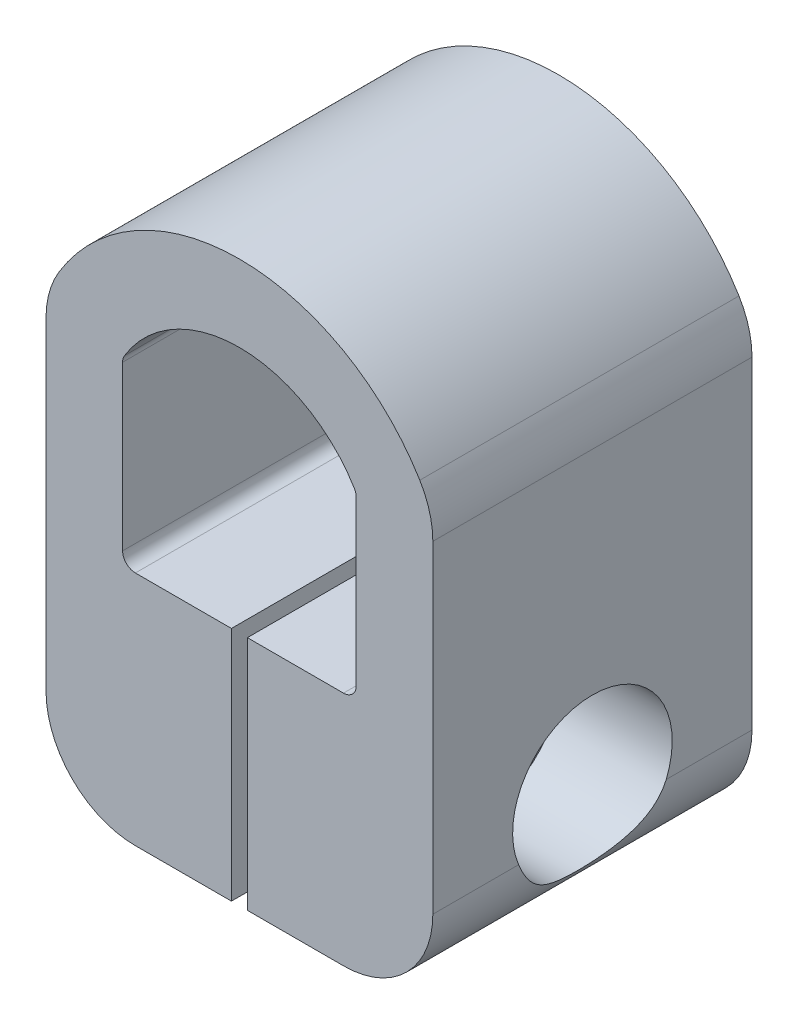
SolidWorks part; units mm, degrees
ref_plane "Front Plane" through (0, 0, 0) normal (0, 0, 1) x (1, 0, 0)
ref_plane "Top Plane" through (0, 0, 0) normal (0, 1, 0) x (1, 0, 0)
ref_plane "Right Plane" through (0, 0, 0) normal (1, 0, 0) x (0, 0, -1)
sketch "Sketch1" plane through (0, 0, 0) normal (0, 0, 1) x (1, 0, 0)
  line L0 (-15.3924, 13.7607) -> (-15.3924, 0.762)
  line L2 (15.3924, 0.762) -> (15.3924, 13.7607)
  line L3 (-9.2964, 13.7607) -> (-9.2964, 0.762)
  line L4 (-8.2804, -0.254) -> (8.2804, -0.254)
  line L5 (9.2964, 0.762) -> (9.2964, 13.7607)
  line L6 (-9.0424, 13.7607) -> (-9.0424, 0.762)
  line L7 (-8.2804, 0) -> (8.2804, 0)
  line L8 (9.0424, 0.762) -> (9.0424, 13.7607)
  line L9 (-8.2804, -19.05) -> (8.2804, -19.05)
  line L10 (-15.3924, 0.762) -> (-15.3924, -11.938)
  line L11 (15.3924, -11.938) -> (15.3924, 0.762)
  line L13 (-8.2804, -6.35) -> (8.2804, -6.35) construction
  arc A2 (15.3924, 13.7607) -> (14.356, 17.4577) centre (8.2804, 13.7607) ccw
  arc A3 (14.356, 17.4577) -> (-14.356, 17.4577) centre (0, 8.7221) ccw
  arc A4 (-14.356, 17.4577) -> (-15.3924, 13.7607) centre (-8.2804, 13.7607) ccw
  arc A5 (-9.2964, 0.762) -> (-8.2804, -0.254) centre (-8.2804, 0.762) ccw
  arc A6 (8.2804, -0.254) -> (9.2964, 0.762) centre (8.2804, 0.762) ccw
  arc A7 (9.2964, 13.7607) -> (9.1483, 14.2889) centre (8.2804, 13.7607) ccw
  arc A8 (9.1483, 14.2889) -> (-9.1483, 14.2889) centre (0, 8.7221) ccw
  arc A9 (-9.1483, 14.2889) -> (-9.2964, 13.7607) centre (-8.2804, 13.7607) ccw
  arc A10 (8.9314, 14.1568) -> (-8.9314, 14.1568) centre (0, 8.7221) ccw
  arc A11 (-8.9314, 14.1568) -> (-9.0424, 13.7607) centre (-8.2804, 13.7607) ccw
  arc A12 (-9.0424, 0.762) -> (-8.2804, 0) centre (-8.2804, 0.762) ccw
  arc A13 (8.2804, 0) -> (9.0424, 0.762) centre (8.2804, 0.762) ccw
  arc A14 (9.0424, 13.7607) -> (8.9314, 14.1568) centre (8.2804, 13.7607) ccw
  arc A15 (-15.3924, -11.938) -> (-8.2804, -19.05) centre (-8.2804, -11.938) ccw
  arc A16 (8.2804, -19.05) -> (15.3924, -11.938) centre (8.2804, -11.938) ccw
  arc A17 (8.2804, -6.35) -> (15.3924, 0.762) centre (8.2804, 0.762) ccw construction
  arc A18 (-15.3924, 0.762) -> (-8.2804, -6.35) centre (-8.2804, 0.762) ccw construction
  dimension "D3" = 12.7
  dimension "D4" = 12.7
  dimension "D1" = 6.35
  dimension "D2" = 0.254
extrude "Boss-Extrude1" add sketch "Sketch1" along normal blind 25.4
sketch "Sketch2" plane through (15.3924, 0, 0) normal (1, 0, 0) x (0, 0, -1)
  line L0 (-25.4, -11.938) -> (-25.4, 13.7607) construction
  line L1 (-25.4, -19.05) -> (0, -19.05) construction
  circle A0 centre (-12.7, -9.525) radius 6.35
  dimension "D2" = 12.7
  dimension "D1" = 12.7
  dimension "D3" = 9.525
extrude "Cut-Extrude1" cut sketch "Sketch2" against normal blind 8.89
sketch "Sketch3" plane through (6.5024, 0, 0) normal (1, 0, 0) x (0, 0, -1)
  circle A0 centre (-12.7, -9.525) radius 3.175
  dimension "D1" = 6.35
extrude "Cut-Extrude2" cut sketch "Sketch3" against normal blind 6.35
sketch "Sketch4" plane through (0, 0, 25.4) normal (0, 0, 1) x (1, 0, 0)
  line L0 (-8.2804, -0.254) -> (8.2804, -0.254) construction
  line L1 (-0.635, -0.254) -> (0, -0.254)
  line L2 (-0.635, -0.254) -> (-0.635, -19.05)
  line L3 (-0.635, -19.05) -> (0, -19.05)
  line L4 (0, -0.254) -> (0, -19.05)
  line L5 (-8.2804, -19.05) -> (8.2804, -19.05) construction
  line L6 (-15.3924, 13.7607) -> (-15.3924, -11.938) construction
  line L7 (-15.3924, -0.254) -> (15.3924, -0.254)
  line L8 (15.3924, -11.938) -> (15.3924, 13.7607) construction
  line L9 (0.635, -0.254) -> (0.635, -19.05)
  line M10 (8.2804, -0.254) -> (-8.2804, -0.254)
  line M13 (-8.2804, -19.05) -> (8.2804, -19.05)
  dimension "D1" = 30.7848
  dimension "D2" = 15.3924
  dimension "D3" = 1.27
  dimension "D4" = 0.635
extrude "Cut-Extrude3" cut sketch "Sketch4" against normal through all contours L9 L7 L4 M13 | L4 L2 M10 M13
sketch "Sketch5" plane through (-0.635, 0, 0) normal (1, 0, 0) x (0, 0, -1)
  circle A0 centre (-12.7, -9.525) radius 3.175 construction
  circle A1 centre (-12.7, -9.525) radius 3.175
  circle A2 centre (-12.7, -9.525) radius 1.905
extrude "Cut-Extrude4" cut sketch "Sketch5" against normal through all contours A2
